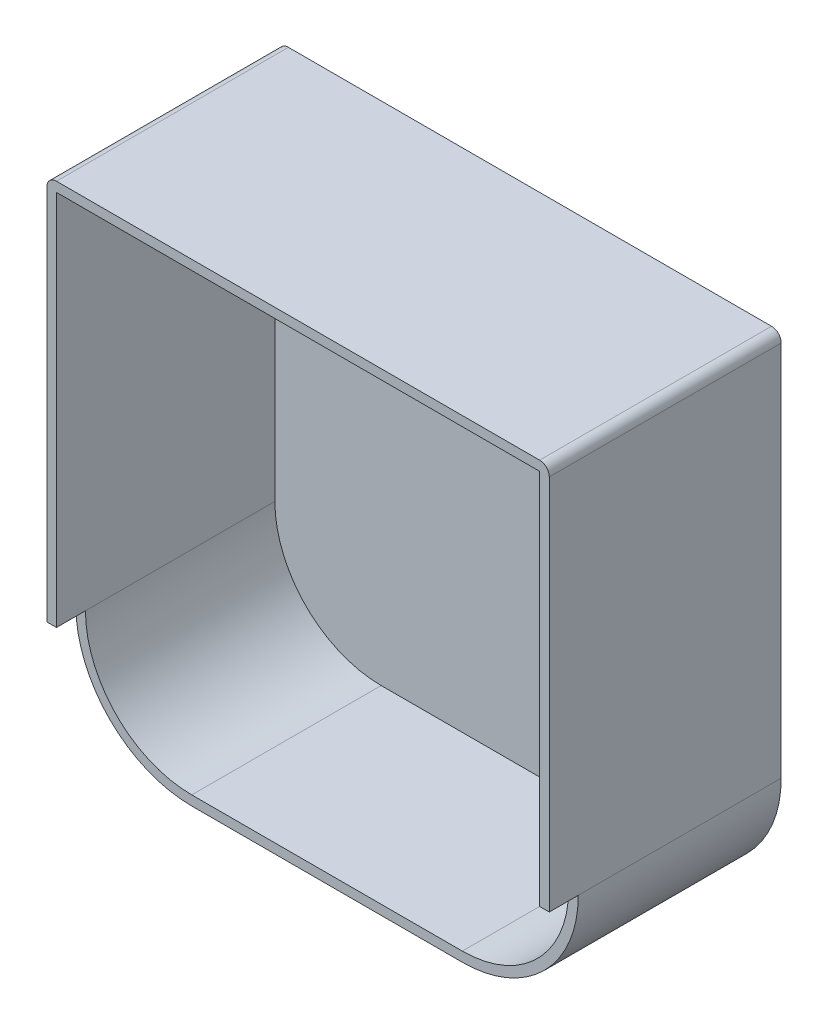
SolidWorks part; units mm, degrees
ref_plane "Plan de face" through (0, 0, 0) normal (0, 0, 1) x (1, 0, 0)
ref_plane "Plan de dessus" through (0, 0, 0) normal (0, 1, 0) x (1, 0, 0)
ref_plane "Plan de droite" through (0, 0, 0) normal (1, 0, 0) x (0, 0, -1)
sketch "Esquisse2" plane through (0, 0, 0) normal (0, 0, 1) x (1, 0, 0)
  line L1 (0, 0) -> (260, 0)
  line L2 (0, 0) -> (0, 260)
  line L3 (0, 260) -> (260, 260)
  line L4 (260, 0) -> (260, 260)
  dimension "D1" = 260
  dimension "D2" = 260
extrude "Boss.-Extru.1" add sketch "Esquisse2" along normal blind 120
fillet "Congé1" radius 60 2 edges at (260, 0, 60) (0, 0, 60)
fillet "Congé2" radius 5 2 edges at (0, 260, 60) (260, 260, 60)
sketch "Esquisse3" plane through (0, 0, 120) normal (0, 0, 1) x (1, 0, 0)
  line L0 (255, 260) -> (5, 260) construction
  line L1 (5, 255) -> (255, 255)
  line L2 (5, 255) -> (5, 60)
  line L3 (60, 5) -> (200, 5)
  line L4 (255, 255) -> (255, 60)
  line L5 (0, 255) -> (0, 60) construction
  line L6 (260, 60) -> (260, 255) construction
  line L8 (60, 0) -> (200, 0) construction
  arc A0 (5, 60) -> (60, 5) centre (60, 60) ccw
  arc A1 (200, 5) -> (255, 60) centre (200, 60) ccw
  point P14 (5, 5)
  dimension "D5" = 55
  dimension "D1" = 5
  dimension "D2" = 5
  dimension "D3" = 5
  dimension "D4" = 5
extrude "Enlèv. mat.-Extru.1" cut sketch "Esquisse3" against normal blind 113
sketch "Esquisse4" plane through (0, 0, 120) normal (0, 0, 1) x (1, 0, 0)
  line L1 (260, 60) -> (0, 60)
  line L2 (260, 60) -> (260, 0)
  line L3 (260, 0) -> (0, 0)
  line L4 (0, 60) -> (0, 0)
extrude "Enlèv. mat.-Extru.2" cut sketch "Esquisse4" against normal blind 15
sketch "Esquisse5" plane through (0, 0, 0) normal (0, 0, -1) x (-1, 0, 0)
  line L0 (-240, 120) -> (-240, 230)
  line L1 (-230, 240) -> (-30, 240)
  line L2 (-20, 230) -> (-20, 120)
  line L3 (-20, 120) -> (-45, 120)
  line L4 (-45, 120) -> (-45, 205)
  line L5 (-55, 215) -> (-205, 215)
  line L6 (-215, 205) -> (-215, 120)
  line L7 (-215, 120) -> (-240, 120)
  line L8 (-60, 0) -> (-200, 0) construction
  line L9 (-260, 60) -> (-260, 255) construction
  line L10 (0, 255) -> (0, 60) construction
  line L11 (-255, 260) -> (-5, 260) construction
  arc A0 (-45, 205) -> (-55, 215) centre (-55, 205) ccw
  arc A1 (-205, 215) -> (-215, 205) centre (-205, 205) ccw
  arc A2 (-30, 240) -> (-20, 230) centre (-30, 230) cw
  arc A3 (-240, 230) -> (-230, 240) centre (-230, 230) cw
  dimension "D8" = 10
  dimension "D1" = 120
  dimension "D2" = 20
  dimension "D3" = 20
  dimension "D4" = 25
  dimension "D5" = 25
  dimension "D6" = 25
  dimension "D7" = 20
extrude "Enlèv. mat.-Extru.3" cut sketch "Esquisse5" against normal blind 4
sketch "Esquisse6" plane through (0, 0, 4) normal (0, 0, -1) x (-1, 0, 0)
  line L0 (-255, 260) -> (-5, 260) construction
  line L1 (-39.5, 238.5) -> (-59.5, 238.5)
  line L3 (-39.5, 216.5) -> (-59.5, 216.5)
  line L5 (0, 255) -> (0, 60) construction
  arc A0 (-39.5, 238.5) -> (-39.5, 216.5) centre (-39.5, 227.5) cw
  arc A1 (-59.5, 216.5) -> (-59.5, 238.5) centre (-59.5, 227.5) cw
  dimension "D1" = 21.5
  dimension "D2" = 39.5
  dimension "D3" = 22
  dimension "D4" = 20
extrude "Enlèv. mat.-Extru.4" cut sketch "Esquisse6" against normal blind 10
